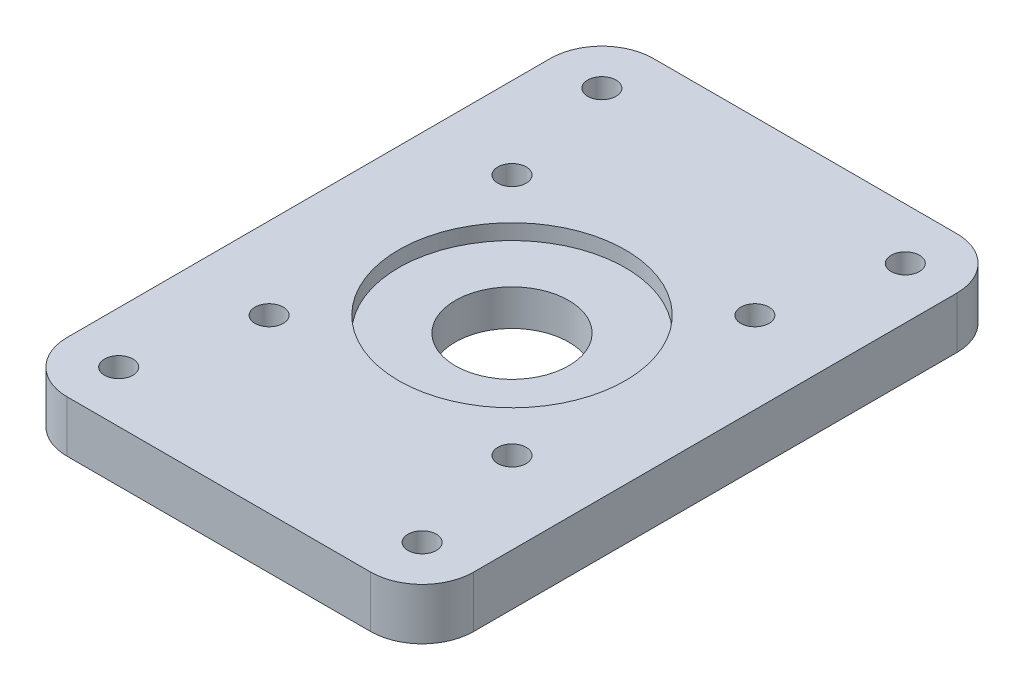
SolidWorks part; units mm, degrees
ref_plane "Front Plane" through (0, 0, 0) normal (0, 0, 1) x (1, 0, 0)
ref_plane "Top Plane" through (0, 0, 0) normal (0, 1, 0) x (1, 0, 0)
ref_plane "Right Plane" through (0, 0, 0) normal (1, 0, 0) x (0, 0, -1)
sketch "Sketch1" plane through (0, 0, 0) normal (0, 1, 0) x (1, 0, 0)
  line L1 (0, 0) -> (58.9, 0)
  line L2 (0, 0) -> (0, 93.78)
  line L3 (0, 93.78) -> (58.9, 93.78)
  line L4 (58.9, 0) -> (58.9, 93.78)
  line L5 (-10, -10) -> (68.9, -10)
  line L6 (-10, -10) -> (-10, 103.78)
  line L7 (-10, 103.78) -> (68.9, 103.78)
  line L8 (68.9, -10) -> (68.9, 103.78)
  line L9 (5.88, 70.46) -> (53.02, 70.46)
  line L10 (5.88, 70.46) -> (5.88, 23.32)
  line L11 (5.88, 23.32) -> (53.02, 23.32)
  line L12 (53.02, 70.46) -> (53.02, 23.32)
  circle A0 centre (0, 93.78) radius 2.75
  circle A1 centre (58.9, 93.78) radius 2.75
  circle A2 centre (58.9, 0) radius 2.75
  circle A3 centre (0, 0) radius 2.75
  circle A4 centre (5.88, 70.46) radius 2.75
  circle A5 centre (53.02, 70.46) radius 2.75
  circle A6 centre (53.02, 23.32) radius 2.75
  circle A7 centre (5.88, 23.32) radius 2.75
  dimension "D7" = 47.14
  dimension "D1" = 93.78
  dimension "D2" = 58.9
  dimension "D3" = 10
  dimension "D4" = 10
  dimension "D5" = 10
  dimension "D6" = 10
  dimension "D8" = 47.14
  dimension "D9" = 15.88
  dimension "D10" = 23.32
extrude "Boss-Extrude1" add sketch "Sketch1" along normal blind 10 contours L5 L8 L7 L6 A3 L2 A0 L3 A1 L4 A2 L1 | A3 L1 A2 L4 A1 L3 A0 L2 A7 L10 A4 L9 A5 L12 A6 L11 | A7 L11 A6 L12 A5 L9 A4 L10
sketch "Sketch2" plane through (0, 10, 0) normal (0, 1, 0) x (1, 0, 0)
  circle A0 centre (29.45, 46.89) radius 11
extrude "Cut-Extrude1" cut sketch "Sketch2" against normal blind 10
sketch "Sketch3" plane through (0, 10, 0) normal (0, 1, 0) x (1, 0, 0)
  circle A0 centre (29.45, 46.89) radius 22
extrude "Cut-Extrude2" cut sketch "Sketch3" against normal blind 3
fillet "Fillet1" radius 10 4 edges at (-10, 5, 10) (68.9, 5, 10) (68.9, 5, -103.78) (-10, 5, -103.78)
